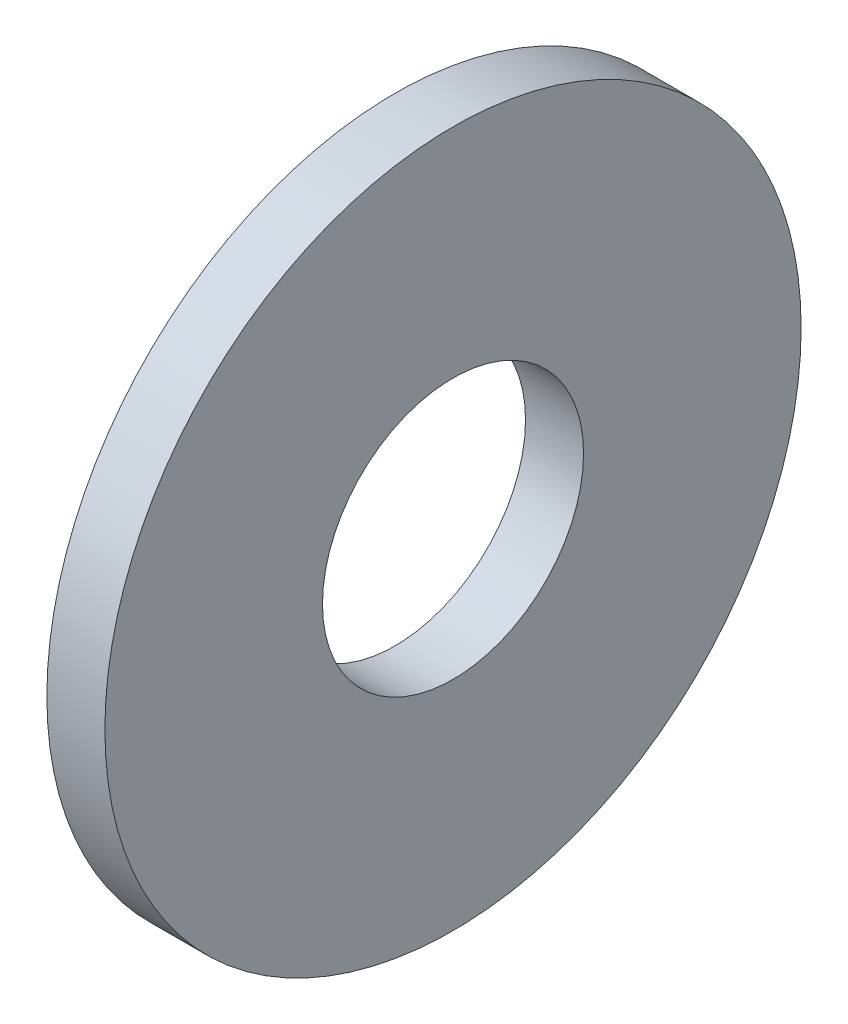
SolidWorks part; units mm, degrees
material "6061-T6 (SS)"
ref_plane "Front Plane" through (0, 0, 0) normal (0, 0, 1) x (1, 0, 0)
ref_plane "Top Plane" through (0, 0, 0) normal (0, 1, 0) x (1, 0, 0)
ref_plane "Right Plane" through (0, 0, 0) normal (1, 0, 0) x (0, 0, -1)
sketch "Sketch1" plane through (0, 0, 0) normal (1, 0, 0) x (0, 0, -1)
  circle A0 centre (0, 0) radius 38.1
  circle A1 centre (0, 0) radius 14.2875
  dimension "D1" = 76.2
  dimension "D2" = 28.575
extrude "Boss-Extrude1" add sketch "Sketch1" along normal mid plane 6.35
